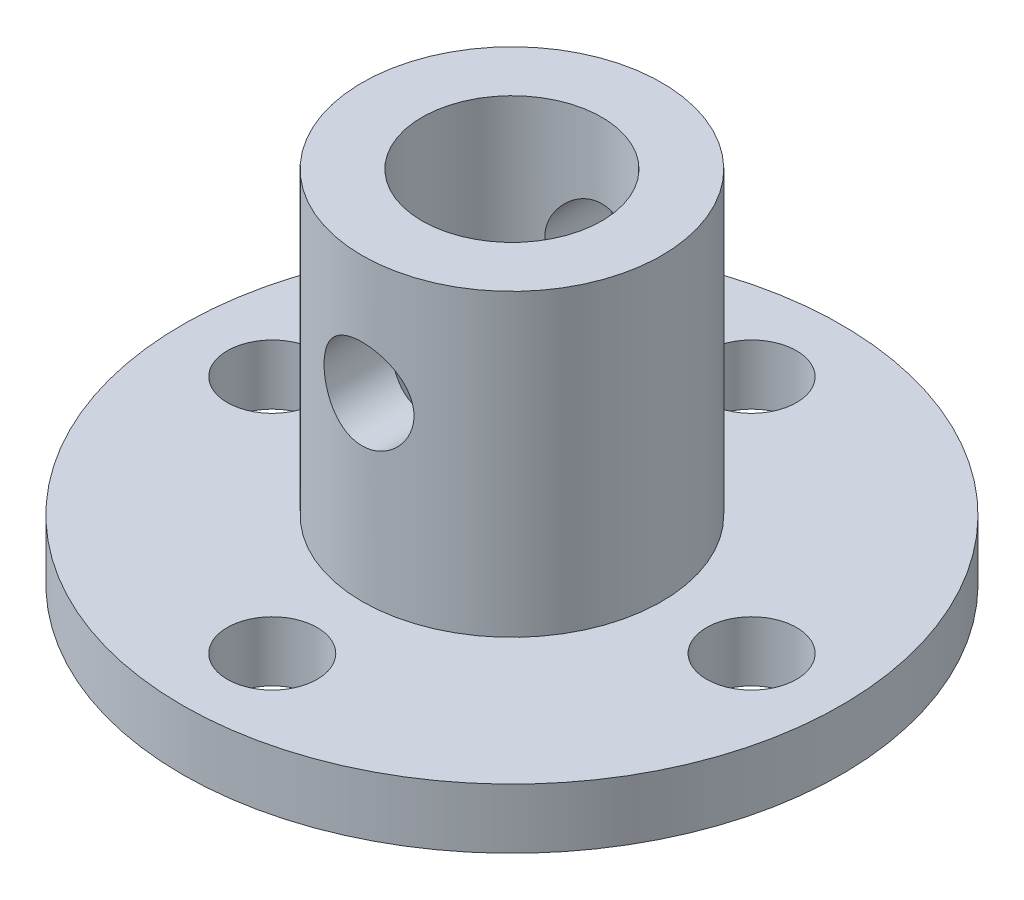
SolidWorks part; units mm, degrees
ref_plane "Front" through (0, 0, 0) normal (0, 0, 1) x (1, 0, 0)
ref_plane "Top" through (0, 0, 0) normal (0, 1, 0) x (1, 0, 0)
ref_plane "Right" through (0, 0, 0) normal (1, 0, 0) x (0, 0, -1)
sketch "Sketch1" plane through (0, 0, 0) normal (0, 1, 0) x (1, 0, 0)
  line L0 (5, 0) -> (11, 0) construction
  circle A0 centre (0, 0) radius 11
  circle A1 centre (0, 0) radius 5 construction
  circle A2 centre (8, 0) radius 1.5
  circle A3 centre (0, -8) radius 1.5
  circle A4 centre (-8, 0) radius 1.5
  circle A5 centre (0, 8) radius 1.5
  circle A6 centre (0, 0) radius 3
  dimension "D1" = 22
  dimension "D2" = 10
  dimension "D3" = 3
  dimension "D5" = 6
  dimension "D4" = 4
extrude "Boss-Extrude1" add sketch "Sketch1" along normal blind 2
sketch "Sketch3" plane through (0, 2, 0) normal (0, 1, 0) x (1, 0, 0)
  circle A0 centre (0, 0) radius 5
  circle A1 centre (0, 0) radius 3
  dimension "D1" = 10
extrude "Boss-Extrude3" add sketch "Sketch3" along normal blind 10
sketch "Sketch4" plane through (0, 0, 0) normal (0, 0, 1) x (1, 0, 0)
  line L0 (0, 0) -> (0, 12) construction
  line L1 (3, 12) -> (-3, 12) construction
  circle A0 centre (0, 8) radius 1.5
  dimension "D1" = 3
  dimension "D2" = 4
extrude "Cut-Extrude1" cut sketch "Sketch4" against normal through all both and the other way through all
